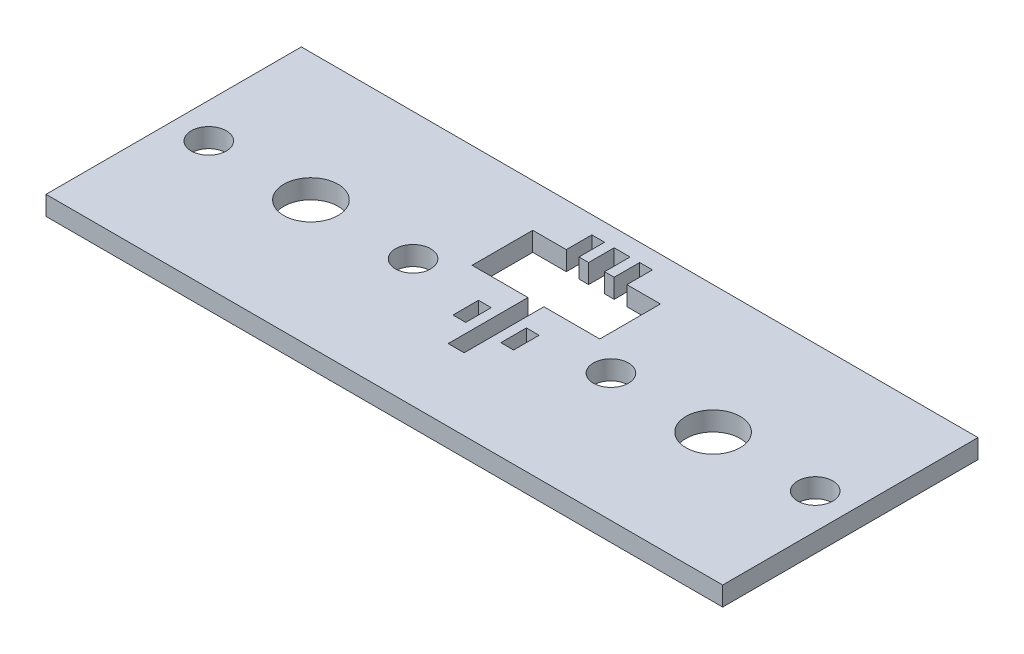
SolidWorks part; units mm, degrees
ref_plane "前视基准面" through (0, 0, 0) normal (0, 0, 1) x (1, 0, 0)
ref_plane "上视基准面" through (0, 0, 0) normal (0, 1, 0) x (1, 0, 0)
ref_plane "右视基准面" through (0, 0, 0) normal (1, 0, 0) x (0, 0, -1)
sketch "草图1" plane through (0, 0, 0) normal (0, 1, 0) x (1, 0, 0)
  line L1 (-53, 20) -> (53, 20)
  line L2 (-53, 20) -> (-53, -20)
  line L3 (-53, -20) -> (53, -20)
  line L4 (53, 20) -> (53, -20)
  line L5 (-53, 20) -> (53, -20) construction
  line L6 (-53, -20) -> (53, 20) construction
  point P0 (0, 0)
  dimension "D1" = 106
  dimension "D2" = 40
extrude "凸台-拉伸1" add sketch "草图1" along normal blind 3
sketch "草图2" plane through (0, 3, 0) normal (0, 1, 0) x (1, 0, 0)
  line L0 (0, -1000) -> (0, 49000) construction
  line L2 (-1031.5, 0) -> (48968.5, 0) construction
  line L3 (-31.5, -995) -> (-31.5, 49005) construction
  line L4 (31.5, -1001) -> (31.5, 48999) construction
  circle A0 centre (-31.5, 0) radius 4.25
  circle A1 centre (31.5, 0) radius 4.25
  circle A2 centre (-47.5, 0) radius 2.75
  circle A3 centre (-15.5, 0) radius 2.75
  circle A4 centre (15.5, 0) radius 2.75
  circle A5 centre (47.5, 0) radius 2.75
  point P9 (0, 0)
  point P23 (0, 0)
  dimension "D1" = 8.5
  dimension "D4" = 5.5
  dimension "D6" = 5.5
  dimension "D2" = 63
  dimension "D5" = 32
  dimension "D7" = 32
extrude "切除-拉伸1" cut sketch "草图2" against normal up to next
sketch "草图3" plane through (0, 3, 0) normal (0, 1, 0) x (1, 0, 0)
  line L0 (0, -1000) -> (0, 49000) construction
  line L1 (-1000, 8.5) -> (49000, 8.5) construction
  line L2 (1.25, 13.25) -> (10, 13.25)
  line L3 (-10, 13.25) -> (-1.25, 13.25)
  line L4 (-10, 13.25) -> (-10, 3.75)
  line L5 (-10, 3.75) -> (-1.25, 3.75)
  line L6 (10, 13.25) -> (10, 3.75)
  line L7 (-10, 13.25) -> (10, 3.75) construction
  line L8 (-10, 3.75) -> (10, 13.25) construction
  line L9 (-1.25, 17.25) -> (1.25, 17.25)
  line L10 (-1.25, 17.25) -> (-1.25, 13.25)
  line L11 (-1.25, -8.75) -> (1.25, -8.75)
  line L12 (1.25, 17.25) -> (1.25, 13.25)
  line L13 (-1.25, 17.25) -> (1.25, -8.75) construction
  line L14 (-1.25, -8.75) -> (1.25, 17.25) construction
  line L15 (-1.25, 3.75) -> (-1.25, -8.75)
  line L16 (1.25, 3.75) -> (10, 3.75)
  line L17 (1.25, 3.75) -> (1.25, -8.75)
  point P4 (0, 8.5)
  point P10 (0, 4.25)
  dimension "D1" = 8.5
  dimension "D2" = 2.5
  dimension "D3" = 9.5
  dimension "D4" = 20
  dimension "D5" = 4
  dimension "D6" = 26
extrude "切除-拉伸2" cut sketch "草图3" against normal up to next
sketch "草图4" plane through (0, 3, 0) normal (0, 1, 0) x (1, 0, 0)
  line L0 (0, -1000) -> (0, 49000) construction
  line L1 (-1001.25, -2.5) -> (48998.75, -2.5) construction
  line L2 (-1.25, 3.75) -> (-1.25, -8.75) construction
  line L3 (-1.25, 13.25) -> (-10, 13.25) construction
  line L4 (1.25, 17.25) -> (-1.25, 17.25) construction
  line L5 (-4.75, 13.25) -> (-2.75, 13.25)
  line L6 (-4.75, 13.25) -> (-4.75, 17.25)
  line L7 (-4.75, 17.25) -> (-2.75, 17.25)
  line L8 (-2.75, 13.25) -> (-2.75, 17.25)
  line L9 (-1.25, 17.25) -> (-1.25, 13.25) construction
  line L10 (4.75, 13.25) -> (4.75, 17.25)
  line L11 (4.75, 13.25) -> (2.75, 13.25)
  line L12 (2.75, 13.25) -> (2.75, 17.25)
  line L13 (4.75, 17.25) -> (2.75, 17.25)
  line L14 (4.75, -0.5) -> (4.75, -4.5)
  line L15 (-4.75, -0.5) -> (-2.75, -0.5)
  line L16 (-4.75, -0.5) -> (-4.75, -4.5)
  line L17 (-4.75, -4.5) -> (-2.75, -4.5)
  line L18 (-2.75, -0.5) -> (-2.75, -4.5)
  line L19 (-4.75, -0.5) -> (-2.75, -4.5) construction
  line L20 (-4.75, -4.5) -> (-2.75, -0.5) construction
  line L21 (4.75, -4.5) -> (2.75, -4.5)
  line L22 (2.75, -0.5) -> (2.75, -4.5)
  line L23 (4.75, -0.5) -> (2.75, -0.5)
  point P8 (-1.25, -2.5)
  point P22 (-3.75, -2.5)
  dimension "D1" = 2
  dimension "D2" = 1.5
  dimension "D3" = 2
  dimension "D4" = 4
  dimension "D5" = 1.5
extrude "切除-拉伸3" cut sketch "草图4" against normal up to next
